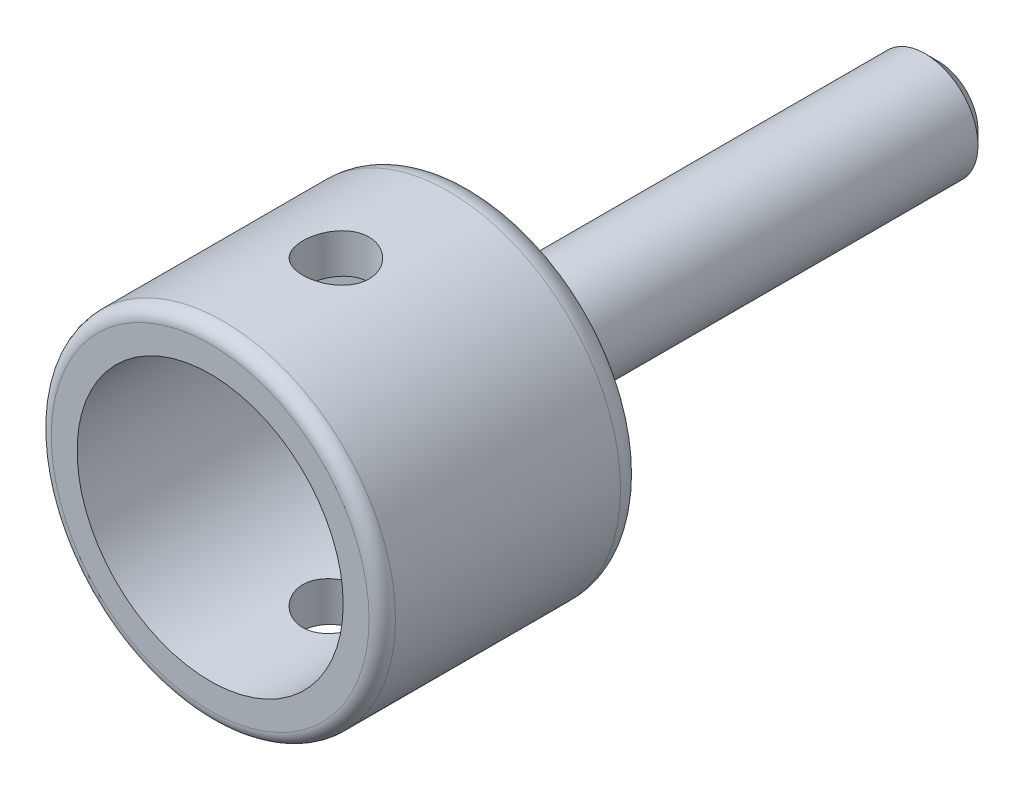
SolidWorks part; units mm, degrees
ref_plane "Front Plane" through (0, 0, 0) normal (0, 0, 1) x (1, 0, 0)
ref_plane "Top Plane" through (0, 0, 0) normal (0, 1, 0) x (1, 0, 0)
ref_plane "Right Plane" through (0, 0, 0) normal (1, 0, 0) x (0, 0, -1)
sketch "Sketch1" plane through (0, 0, 0) normal (0, 0, 1) x (1, 0, 0)
  circle A0 centre (0, 0) radius 13
  dimension "D1" = 26
extrude "Boss-Extrude1" add sketch "Sketch1" along normal blind 20
sketch "Sketch2" plane through (0, 0, 20) normal (0, 0, 1) x (1, 0, 0)
  circle A0 centre (0, 0) radius 10.05
  dimension "D1" = 20.1
extrude "Cut-Extrude1" cut sketch "Sketch2" against normal blind 15
sketch "Sketch3" plane through (0, 0, 0) normal (0, 0, -1) x (-1, 0, 0)
  circle A0 centre (0, 0) radius 4
  dimension "D1" = 8
extrude "Boss-Extrude2" add sketch "Sketch3" along normal blind 35
fillet "Fillet1" radius 2 2 edges at (-4, 0, 0) (13, 0, 0)
chamfer "Chamfer1" distance 1 angle 45 1 edges at (-4, 0, -35)
fillet "Fillet2" radius 1 1 edges at (13, 0, 20)
sketch "Sketch4" plane through (0, 0, 0) normal (0, 1, 0) x (1, 0, 0)
  line L0 (-13, -10.5) -> (13, -10.5) construction
  line L1 (-13, -2) -> (-13, -19) construction
  line L2 (13, -19) -> (13, -2) construction
  line L3 (0, -2) -> (0, -19) construction
  line L4 (13, -2) -> (-13, -2) construction
  line L5 (13, -19) -> (-13, -19) construction
  circle A0 centre (0, -10.5) radius 2.5
  point P14 (0.4233, -11.5237)
  point P15 (0, 0)
  point P16 (0, -10.5)
  point P17 (0, 0)
  dimension "D1" = 5
extrude "Cut-Extrude2" cut sketch "Sketch4" against normal mid plane 40
